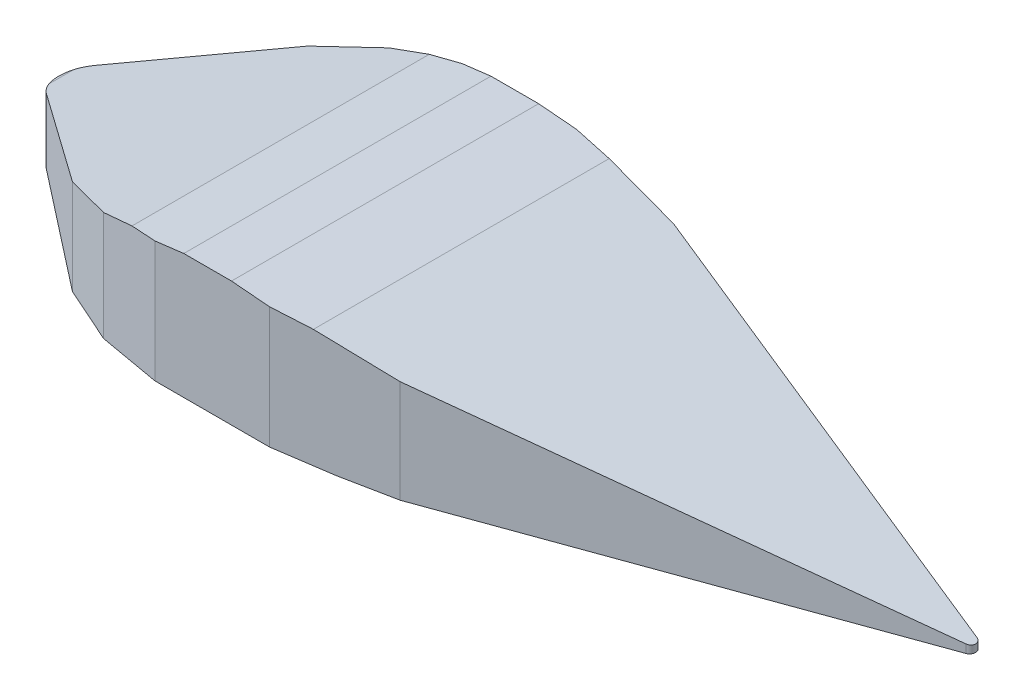
SolidWorks part; units mm, degrees
ref_plane "Front Plane" through (0, 0, 0) normal (0, 0, 1) x (1, 0, 0)
ref_plane "Top Plane" through (0, 0, 0) normal (0, 1, 0) x (1, 0, 0)
ref_plane "Right Plane" through (0, 0, 0) normal (1, 0, 0) x (0, 0, -1)
sketch "Sketch1" plane through (0, 0, 0) normal (0, 1, 0) x (1, 0, 0)
  line L0 (161.4098, 126.0887) -> (784.13, 612.54)
  line L1 (784.13, 612.54) -> (1076.464, 742.696)
  line L2 (1076.464, 742.696) -> (1401.451, 800)
  line L3 (1401.451, 800) -> (1997.019, 800)
  line L4 (1997.019, 800) -> (2590.582, 712.35)
  line L5 (2590.582, 712.35) -> (4854.8761, 28.7196)
  line L6 (4854.8761, -28.7196) -> (2590.582, -712.35)
  line L7 (2590.582, -712.35) -> (1997.019, -800)
  line L8 (1997.019, -800) -> (1401.451, -800)
  line L9 (1401.451, -800) -> (1076.464, -742.696)
  line L10 (1076.464, -742.696) -> (784.13, -612.54)
  line L11 (784.13, -612.54) -> (161.4098, -126.0887)
  arc A0 (161.4098, 126.0887) -> (161.4098, -126.0887) centre (259.9067, 0) ccw
  arc A1 (4854.8761, 28.7196) -> (4854.8761, -28.7196) centre (4846.2052, 0) cw
  point P15 (0, 0)
  point P18 (4950, 0)
  dimension "r0" = 160
  dimension "r6" = 30
  dimension "x1" = 784.13
  dimension "x2" = 1076.464
  dimension "x3" = 1401.451
  dimension "x4" = 1997.019
  dimension "x5" = 2590.582
  dimension "x6" = 4950
  dimension "x7" = 2590.582
  dimension "x8" = 1997.019
  dimension "x9" = 1401.451
  dimension "x10" = 1076.464
  dimension "x11" = 784.13
  dimension "y1" = 612.54
  dimension "y2" = 742.696
  dimension "y3" = 800
  dimension "y5" = 712.35
  dimension "y7" = 712.35
  dimension "y8" = 800
  dimension "y10" = 742.696
  dimension "y11" = 612.54
extrude "TopView_Extrude" add sketch "Sketch1" along normal blind 800
sketch "Sketch2" plane through (0, 0, 0) normal (0, 0, 1) x (1, 0, 0)
  line L0 (0, 300) -> (0, 332.8541)
  line L1 (113.6551, 478.3843) -> (1255.921, 763.655)
  line L2 (1255.921, 763.655) -> (1551.451, 800)
  line L3 (1551.451, 800) -> (1800, 800)
  line L4 (1800, 800) -> (2197.056, 765.81)
  line L5 (2197.056, 765.81) -> (4950, 288.165)
  line L6 (4950, 288.165) -> (4950, 265.638)
  line L7 (4950, 265.638) -> (2301.451, 150)
  line L8 (2301.451, 150) -> (150, 150)
  arc A0 (0, 300) -> (150, 150) centre (150, 300) ccw
  arc A1 (0, 332.8541) -> (113.6551, 478.3843) centre (150, 332.8541) cw
  point P12 (0, 150)
  point P15 (0, 450)
  dimension "r0" = 150
  dimension "r1" = 150
  dimension "x2" = 1255.921
  dimension "x3" = 1551.451
  dimension "x4" = 1800
  dimension "x5" = 2197.056
  dimension "x6" = 4950
  dimension "x8" = 2301.451
  dimension "y0" = 150
  dimension "y1" = 450
  dimension "y2" = 763.655
  dimension "y3" = 800
  dimension "y5" = 765.81
  dimension "y6" = 288.165
  dimension "y7" = 265.638
extrude "SideProfile_Cut" cut sketch "Sketch2" against normal through all and the other way through all flip side to cut
